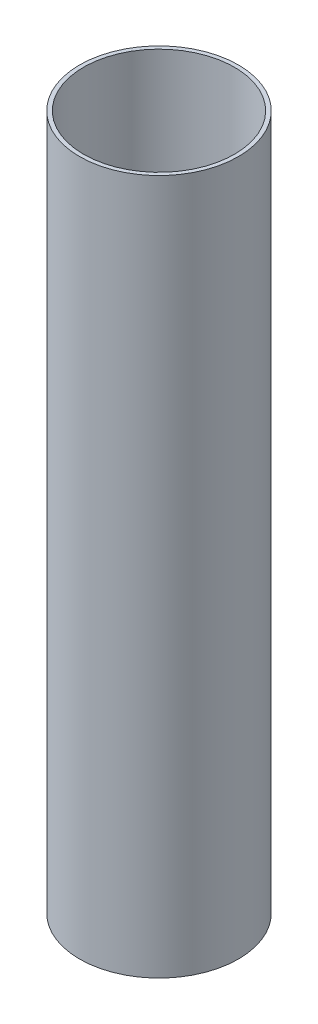
SolidWorks part; units mm, degrees
ref_plane "Front Plane" through (0, 0, 0) normal (0, 0, 1) x (1, 0, 0)
ref_plane "Top Plane" through (0, 0, 0) normal (0, 1, 0) x (1, 0, 0)
ref_plane "Right Plane" through (0, 0, 0) normal (1, 0, 0) x (0, 0, -1)
sketch "Sketch1" plane through (0, 0, 0) normal (0, 1, 0) x (1, 0, 0)
  circle A0 centre (0, 0) radius 40
  circle A1 centre (0, 0) radius 38
  dimension "D1" = 80
  dimension "D2" = 76
extrude "Boss-Extrude1" add sketch "Sketch1" along normal blind 350
equation "\"Dext\"=80"
equation "\"D1@Sketch1\"=\"Dext\""
equation "\"Dint\"=76"
equation "\"D2@Sketch1\"=\"Dint\""
equation "\"Length\"= 350"
equation "\"D1@Boss-Extrude1\"=\"Length\""
